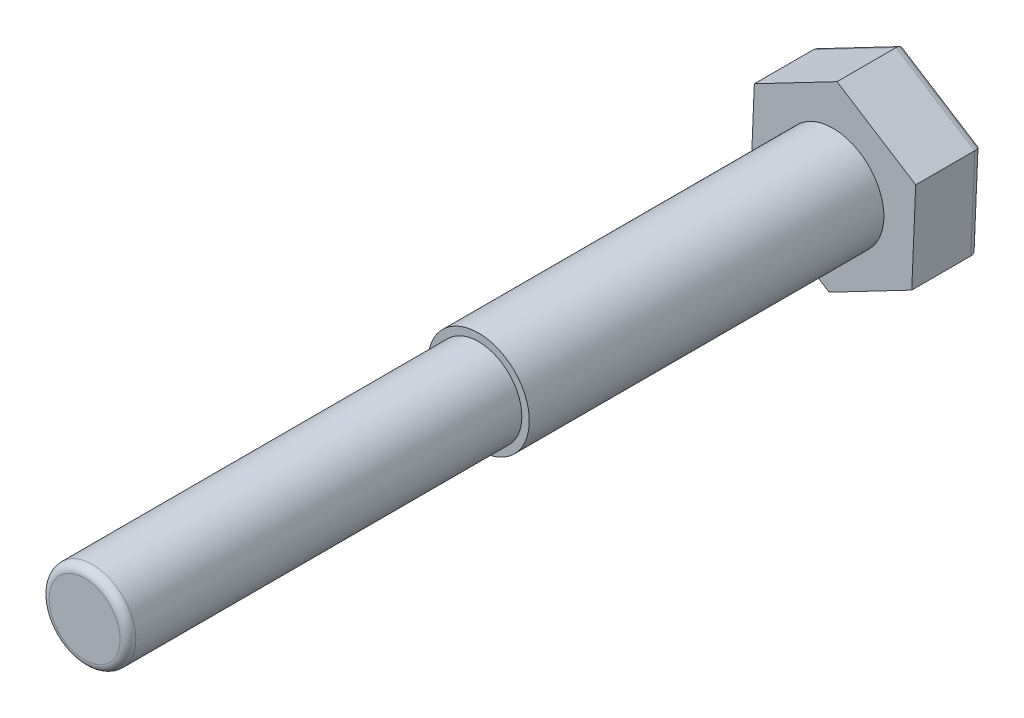
SolidWorks part; units mm, degrees
ref_plane "前视" through (0, 0, 0) normal (0, 0, 1) x (1, 0, 0)
ref_plane "上视" through (0, 0, 0) normal (0, 1, 0) x (1, 0, 0)
ref_plane "右视" through (0, 0, 0) normal (1, 0, 0) x (0, 0, -1)
sketch "草图1" plane through (0, 0, 0) normal (0, 0, 1) x (1, 0, 0)
  line L1 (20.9842, 10.9543) -> (1.0054, 23.65)
  line L2 (1.0054, 23.65) -> (-19.9788, 12.6957)
  line L3 (-19.9788, 12.6957) -> (-20.9842, -10.9543)
  line L4 (-20.9842, -10.9543) -> (-1.0054, -23.65)
  line L5 (-1.0054, -23.65) -> (19.9788, -12.6957)
  line L6 (19.9788, -12.6957) -> (20.9842, 10.9543)
  circle A0 centre (0, 0) radius 20.5 construction
  dimension "D1" = 47.3
  dimension "D2" = 41
extrude "基体-拉伸" add sketch "草图1" along normal blind 17
sketch "草图2" plane through (0, 0, 17) normal (0, 0, 1) x (1, 0, 0)
  circle A0 centre (0, 0) radius 12.9
  dimension "D1" = 25.8
extrude "凸台-拉伸1" add sketch "草图2" along normal blind 90
fillet "圆角3" radius 2 6 edges at (9.4867, -18.1729, 0) (-10.9948, -17.3021, 0) (-20.4815, 0.8707, 0) (-9.4867, 18.1729, 0) (10.9948, 17.3021, 0) (20.4815, -0.8707, 0)
sketch "草图3" plane through (0, 0, 107) normal (0, 0, 1) x (1, 0, 0)
  circle A0 centre (0, 0) radius 11
  dimension "D1" = 22
extrude "凸台-拉伸2" add sketch "草图3" along normal blind 100
fillet "圆角4" radius 2 1 edges at (11, 0, 207)
